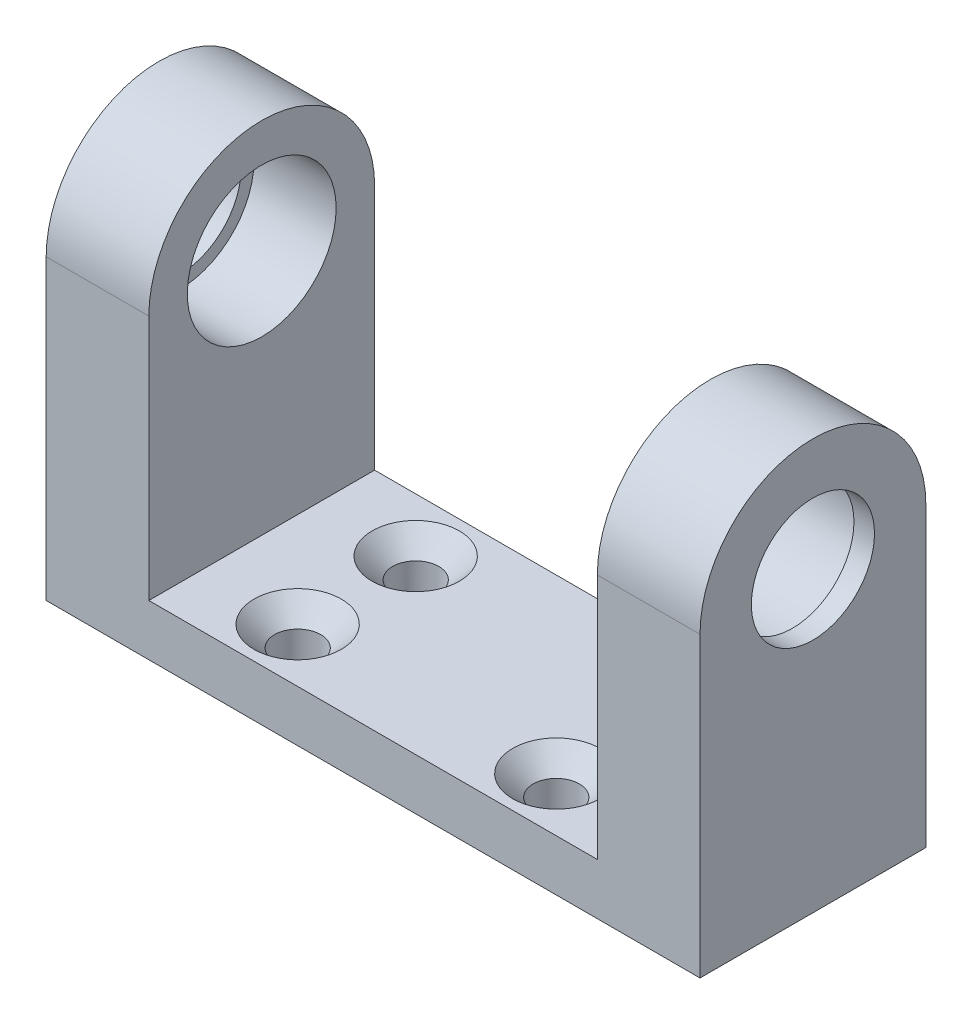
SolidWorks part; units mm, degrees
ref_plane "Front Plane" through (0, 0, 0) normal (0, 0, 1) x (1, 0, 0)
ref_plane "Top Plane" through (0, 0, 0) normal (0, 1, 0) x (1, 0, 0)
ref_plane "Right Plane" through (0, 0, 0) normal (1, 0, 0) x (0, 0, -1)
sketch "Sketch1" plane through (0, 0, 0) normal (0, 0, 1) x (1, 0, 0)
  line L0 (-19.25, 20) -> (-19.25, -20)
  line L1 (-19.25, -20) -> (44.45, -20)
  line L2 (44.45, -20) -> (44.45, 20)
  line L3 (44.45, 20) -> (34.45, 20)
  line L4 (34.45, 20) -> (34.45, -15)
  line L5 (34.45, -15) -> (-9.25, -15)
  line L6 (-9.25, -15) -> (-9.25, 20)
  line L7 (-9.25, 20) -> (-19.25, 20)
  line L9 (-4.25, -1) -> (4.25, -1) construction
  line L10 (-4.25, -1) -> (-4.25, 15) construction
  line L11 (-4.25, 15) -> (4.25, 15) construction
  line L12 (4.25, -1) -> (4.25, 15) construction
  line L13 (-4.25, -1) -> (4.25, 15) construction
  line L14 (-4.25, 15) -> (4.25, -1) construction
  point P0 (44.45, 0)
  point P13 (0, 7)
  dimension "D1" = 10
  dimension "D2" = 5
  dimension "D3" = 44.45
  dimension "D4" = 35
  dimension "D5" = 8.5
  dimension "D6" = 16
  dimension "D7" = 5
  dimension "D8" = 5
extrude "Boss-Extrude1" add sketch "Sketch1" along normal mid plane 22
sketch "Sketch2" plane through (44.45, 0, 0) normal (1, 0, 0) x (0, 0, -1)
  line L0 (-11, 20) -> (11, 20) construction
  line L1 (-11, -20) -> (-11, 20) construction
  line L2 (11, -20) -> (11, 20) construction
  line L3 (-11, 9) -> (-11, 20)
  line L5 (11, 9) -> (11, 20)
  line L7 (-11, 20) -> (-11, 31)
  line L8 (-11, 31) -> (11, 31)
  line L9 (11, 31) -> (11, 20)
  circle A0 centre (0, 9) radius 6
  arc A1 (0, 20) -> (-11, 9) centre (0, 9) ccw
  arc A2 (0, 20) -> (11, 9) centre (0, 9) cw
  point P5 (0, 15)
  dimension "D1" = 12
extrude "Cut-Extrude1" cut sketch "Sketch2" against normal through all
sketch "Sketch3" plane through (0, -15, 0) normal (0, 1, 0) x (1, 0, 0)
  line L0 (0, 5.75) -> (0, -5.75) construction
  line L1 (34.45, -11) -> (-9.25, -11) construction
  line L2 (0, 5.75) -> (25.2, 5.75) construction
  line L3 (25.2, 5.75) -> (25.2, -5.75) construction
  line L4 (25.2, -5.75) -> (0, -5.75) construction
  line L5 (34.45, 11) -> (-9.25, 11) construction
  circle A0 centre (0, 5.75) radius 2.25
  circle A1 centre (0, -5.75) radius 2.25
  circle A2 centre (25.2, 5.75) radius 2.25
  circle A3 centre (25.2, -5.75) radius 2.25
  point P7 (0, -8)
  point P8 (12.6, 5.75)
  point P13 (12.6, 11)
  dimension "D1" = 4.5
  dimension "D2" = 3
extrude "Cut-Extrude2" cut sketch "Sketch3" against normal through all
chamfer "Chamfer1" distance 2 angle 45 4 edges at (0, -15, -3.5) (0, -15, 8) (25.2, -15, -3.5) (25.2, -15, 8)
sketch "Sketch4" plane through (44.45, 0, 0) normal (1, 0, 0) x (0, 0, -1)
  circle A0 centre (0, 9) radius 7.25
  dimension "D1" = 14.5
extrude "Cut-Extrude3" cut sketch "Sketch4" against normal offset from surface (59.7 mm away) 2 from offset 2
